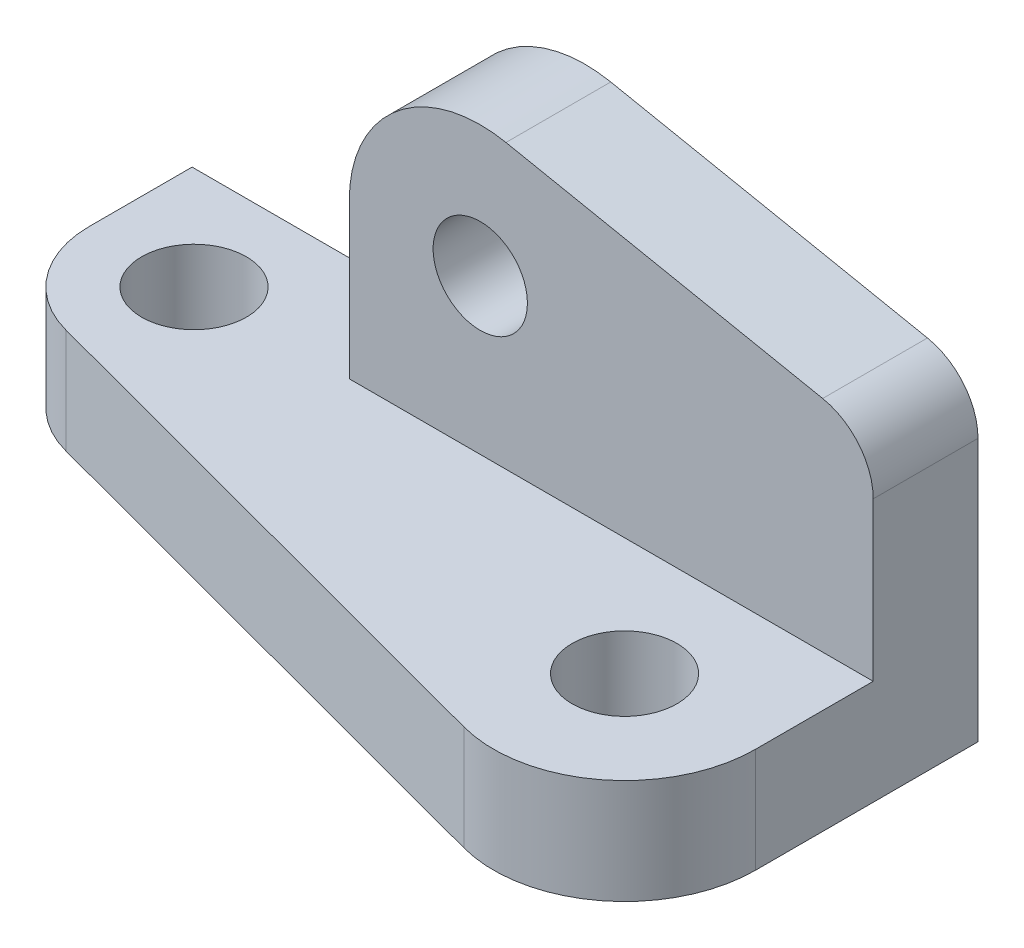
SolidWorks part; units mm, degrees
ref_plane "Front Plane" through (0, 0, 0) normal (0, 0, 1) x (1, 0, 0)
ref_plane "Top Plane" through (0, 0, 0) normal (0, 1, 0) x (1, 0, 0)
ref_plane "Right Plane" through (0, 0, 0) normal (1, 0, 0) x (0, 0, -1)
sketch "Sketch1" plane through (0, 0, 0) normal (0, 1, 0) x (1, 0, 0)
  line L0 (0, 0) -> (0, 35)
  line L1 (0, 35) -> (150, 35)
  line L2 (150, 35) -> (150, -40)
  line L3 (150, -40) -> (0, 0)
  dimension "D1" = 35
  dimension "D2" = 150
  dimension "D3" = 75
extrude "Boss-Extrude1" add sketch "Sketch1" along normal blind 20
sketch "Sketch2" plane through (0, 0, -35) normal (0, 0, -1) x (-1, 0, 0)
  line L0 (-150, 0) -> (-150, 60)
  line L1 (-150, 60) -> (-50, 80)
  line L2 (-50, 80) -> (-50, 0)
  line L3 (-150, 0) -> (0, 0) construction
  line L4 (-50, 0) -> (-150, 0)
  dimension "D1" = 60
  dimension "D2" = 80
  dimension "D3" = 100
extrude "Boss-Extrude2" add sketch "Sketch2" against normal blind 20
fillet "Fillet1" radius 20 1 edges at (0, 10, 0)
fillet "Fillet2" radius 25 2 edges at (150, 10, 40) (50, 80, -25)
fillet "Fillet3" radius 12 1 edges at (150, 60, -25)
hole_wizard "Ø20.0 (20) Diameter Hole1" positions "Sketch5" profile "Sketch6" hole size "Ø20.0" standard "ANSI Metric" end condition through all
sketch "Sketch5" plane through (0, 20, 0) normal (0, 1, 0) x (1, 0, 0)
  arc A0 (0, 15.3656) -> (14.8467, -3.9591) centre (20, 15.3656) ccw construction
  arc A1 (118.5584, -31.6156) -> (150, -7.4597) centre (125, -7.4597) ccw construction
  point P0 (20, 15.3656)
  point P2 (125, -7.4597)
  point P5 (0, 0)
  point P9 (0, 0)
sketch "Sketch6" plane through (20, 20, -15.3656) normal (1, 0, 0) x (0, 0, 1)
  line L0 (0, 0) -> (0, 20)
  line L1 (0, 20) -> (10, 20)
  line L2 (10, 20) -> (10, 0)
  line L5 (10, 0) -> (0, 0)
  line L11 (0, -6.35) -> (0, 107.95) construction
  dimension "Thru Hole Dia." = 20
  dimension "Thru Hole Depth" = 20
hole_wizard "Ø18.0 (18) Diameter Hole1" positions "Sketch7" profile "Sketch8" hole size "Ø18.0" standard "ANSI Metric" end condition through all
sketch "Sketch7" plane through (0, 0, -15) normal (0, 0, 1) x (1, 0, 0)
  arc A0 (79.9029, 74.0194) -> (50, 49.5049) centre (75, 49.5049) ccw construction
  point P0 (75, 49.5049)
  point P3 (0, 0)
sketch "Sketch8" plane through (75, 49.5049, -15) normal (1, 0, 0) x (0, -1, 0)
  line L0 (0, 0) -> (0, 20)
  line L1 (0, 20) -> (9, 20)
  line L2 (9, 20) -> (9, 0)
  line L5 (9, 0) -> (0, 0)
  line L11 (0, -6.35) -> (0, 107.95) construction
  dimension "Thru Hole Dia." = 18
  dimension "Thru Hole Depth" = 20
